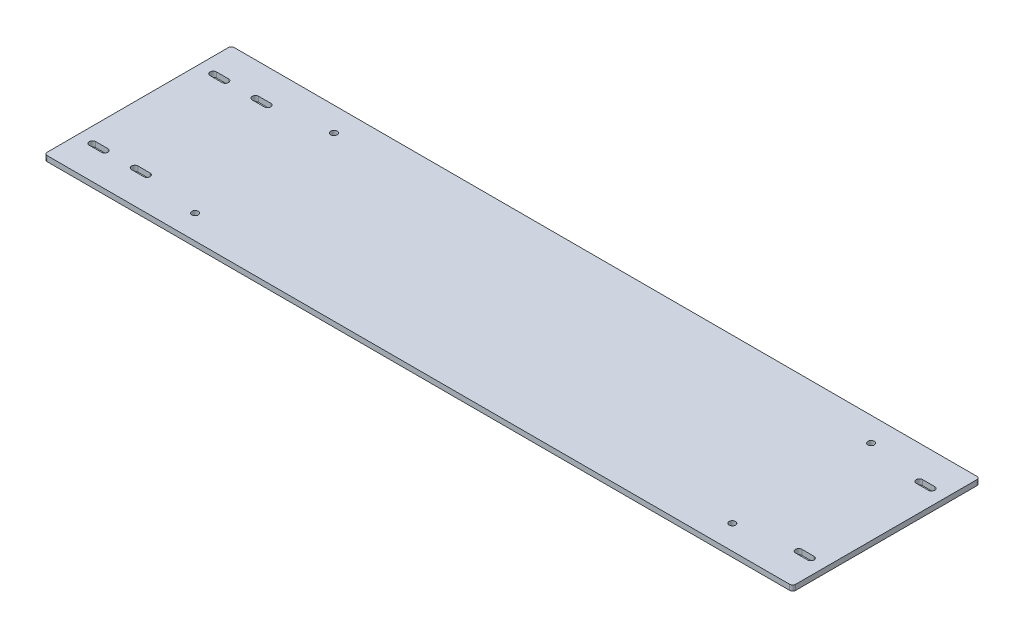
SolidWorks part; units mm, degrees
material "PC High Viscosity"
ref_plane "Front" through (0, 0, 0) normal (0, 0, 1) x (1, 0, 0)
ref_plane "Top" through (0, 0, 0) normal (0, 1, 0) x (1, 0, 0)
ref_plane "Right" through (0, 0, 0) normal (1, 0, 0) x (0, 0, -1)
sketch "Sketch1" plane through (0, 0, 0) normal (0, 1, 0) x (1, 0, 0)
  line L0 (15.875, 34.925) -> (28.575, 34.925) construction
  line L1 (0, 0) -> (787.4, 0)
  line L2 (0, 0) -> (0, 196.85)
  line L3 (0, 196.85) -> (787.4, 196.85)
  line L4 (787.4, 0) -> (787.4, 196.85)
  line L5 (15.875, 38.3032) -> (28.575, 38.3032)
  line L6 (15.875, 31.5468) -> (28.575, 31.5468)
  line L7 (22.225, 34.925) -> (22.225, 161.925) construction
  line L8 (15.875, 161.925) -> (28.575, 161.925) construction
  line L9 (15.875, 165.3032) -> (28.575, 165.3032)
  line L10 (15.875, 158.5468) -> (28.575, 158.5468)
  line L11 (22.225, 161.925) -> (66.675, 161.925) construction
  line L12 (66.675, 161.925) -> (66.675, 34.925) construction
  line L13 (66.675, 34.925) -> (22.225, 34.925) construction
  line L14 (60.325, 161.925) -> (73.025, 161.925) construction
  line L15 (60.325, 165.3032) -> (73.025, 165.3032)
  line L16 (60.325, 158.5468) -> (73.025, 158.5468)
  line L17 (60.325, 34.925) -> (73.025, 34.925) construction
  line L18 (60.325, 38.3032) -> (73.025, 38.3032)
  line L19 (60.325, 31.5468) -> (73.025, 31.5468)
  line L20 (765.175, 161.925) -> (765.175, 34.925) construction
  line L21 (771.525, 161.925) -> (758.825, 161.925) construction
  line L22 (771.525, 158.5468) -> (758.825, 158.5468)
  line L23 (771.525, 165.3032) -> (758.825, 165.3032)
  line L24 (771.525, 34.925) -> (758.825, 34.925) construction
  line L25 (771.525, 31.5468) -> (758.825, 31.5468)
  line L26 (771.525, 38.3032) -> (758.825, 38.3032)
  arc A0 (15.875, 38.3032) -> (15.875, 31.5468) centre (15.875, 34.925) ccw
  arc A1 (28.575, 31.5468) -> (28.575, 38.3032) centre (28.575, 34.925) ccw
  arc A2 (15.875, 165.3032) -> (15.875, 158.5468) centre (15.875, 161.925) ccw
  arc A3 (28.575, 158.5468) -> (28.575, 165.3032) centre (28.575, 161.925) ccw
  arc A4 (60.325, 165.3032) -> (60.325, 158.5468) centre (60.325, 161.925) ccw
  arc A5 (73.025, 158.5468) -> (73.025, 165.3032) centre (73.025, 161.925) ccw
  arc A6 (60.325, 38.3032) -> (60.325, 31.5468) centre (60.325, 34.925) ccw
  arc A7 (73.025, 31.5468) -> (73.025, 38.3032) centre (73.025, 34.925) ccw
  arc A8 (771.525, 158.5468) -> (771.525, 165.3032) centre (771.525, 161.925) ccw
  arc A9 (758.825, 165.3032) -> (758.825, 158.5468) centre (758.825, 161.925) ccw
  arc A10 (771.525, 31.5468) -> (771.525, 38.3032) centre (771.525, 34.925) ccw
  arc A11 (758.825, 38.3032) -> (758.825, 31.5468) centre (758.825, 34.925) ccw
  point P7 (22.225, 34.925)
  point P13 (22.225, 161.925)
  point P25 (66.675, 161.925)
  point P31 (66.675, 34.925)
  point P40 (765.175, 161.925)
  point P47 (765.175, 34.925)
  dimension "D1" = 6.7564
  dimension "D2" = 34.925
  dimension "D3" = 12.7
  dimension "D4" = 22.225
  dimension "D5" = 127
  dimension "D6" = 34.925
  dimension "D7" = 44.45
  dimension "D8" = 22.225
  dimension "D9" = 698.5
extrude "Boss-Extrude1" add sketch "Sketch1" along normal blind 5.588
fillet "Fillet1" radius 3.175 4 edges at (0, 2.794, -196.85) (787.4, 2.794, -196.85) (0, 2.794, 0) (787.4, 2.794, 0)
sketch "Sketch2" plane through (0, 5.588, 0) normal (0, 1, 0) x (1, 0, 0)
  line L0 (0, 98.425) -> (787.4, 98.425) construction
  line L1 (0, 193.675) -> (0, 3.175) construction
  line L2 (787.4, 3.175) -> (787.4, 193.675) construction
  line L3 (784.225, 196.85) -> (3.175, 196.85) construction
  line L4 (133.35, 25.4) -> (698.5, 25.4) construction
  line L5 (133.35, 25.4) -> (133.35, 171.45) construction
  line L6 (133.35, 171.45) -> (698.5, 171.45) construction
  line L7 (698.5, 25.4) -> (698.5, 171.45) construction
  line L8 (133.35, 25.4) -> (698.5, 171.45) construction
  line L9 (133.35, 171.45) -> (698.5, 25.4) construction
  line L10 (73.025, 161.925) -> (133.35, 161.925) construction
  line L11 (758.825, 161.925) -> (698.5, 161.925) construction
  circle A0 centre (133.35, 171.45) radius 3.3782
  circle A1 centre (133.35, 25.4) radius 3.3782
  circle A2 centre (698.5, 25.4) radius 3.3782
  circle A3 centre (698.5, 171.45) radius 3.3782
  point P6 (415.925, 98.425)
  dimension "D2" = 6.7564
  dimension "D1" = 88.9
  dimension "D3" = 25.4
extrude "Cut-Extrude1" cut sketch "Sketch2" against normal through all
